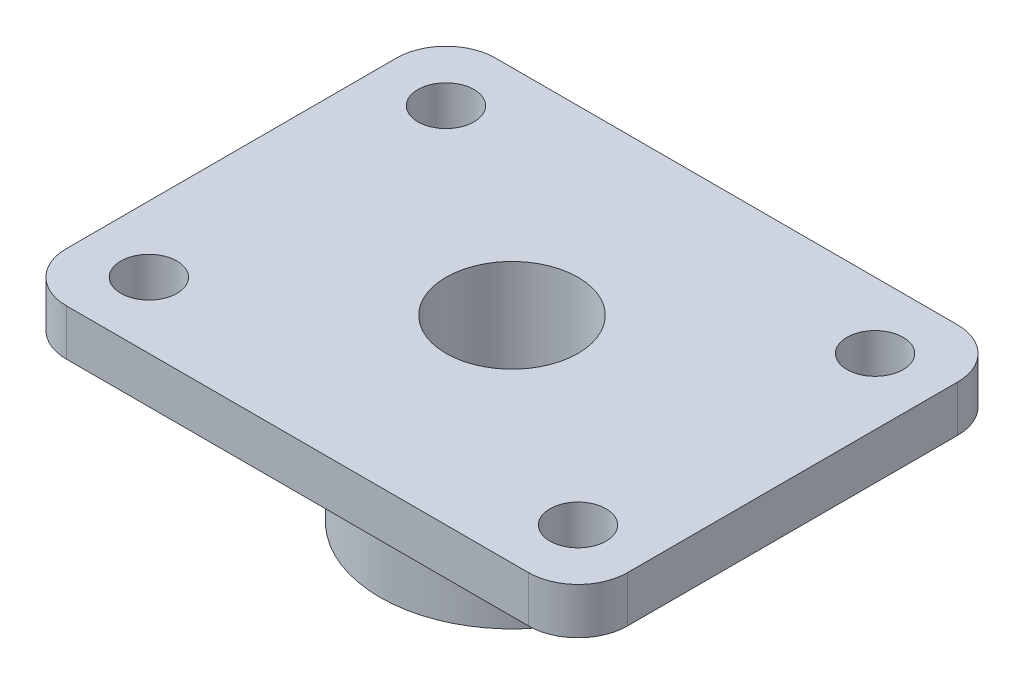
SolidWorks part; units mm, degrees
material "Acciaio al carbonio semplice"
ref_plane "Piano frontale" through (0, 0, 0) normal (0, 0, 1) x (1, 0, 0)
ref_plane "Piano superiore" through (0, 0, 0) normal (0, 1, 0) x (1, 0, 0)
ref_plane "Piano destro" through (0, 0, 0) normal (1, 0, 0) x (0, 0, -1)
sketch "Schizzo1" plane through (0, 0, 0) normal (0, 1, 0) x (1, 0, 0)
  line L0 (0, 0) -> (85, 0) construction
  line L1 (-70, 65) -> (70, 65)
  line L2 (-85, 50) -> (-85, -50)
  line L3 (-70, -65) -> (70, -65)
  line L4 (85, 50) -> (85, -50)
  line L5 (-85, 65) -> (85, -65) construction
  line L6 (-85, -65) -> (85, 65) construction
  line L7 (0, 0) -> (0, -65) construction
  circle A0 centre (0, 0) radius 20
  circle A1 centre (65, -45) radius 8.5
  arc A2 (70, -65) -> (85, -50) centre (70, -50) ccw
  circle A3 centre (65, 45) radius 8.5
  circle A4 centre (-65, -45) radius 8.5
  circle A5 centre (-65, 45) radius 8.5
  arc A6 (-85, -50) -> (-70, -65) centre (-70, -50) ccw
  arc A7 (70, 65) -> (85, 50) centre (70, 50) cw
  arc A8 (-70, 65) -> (-85, 50) centre (-70, 50) ccw
  point P0 (0, 0)
  dimension "D3" = 40
  dimension "D4" = 17
  dimension "D7" = 15
  dimension "D8" = 15
  dimension "D1" = 170
  dimension "D2" = 130
  dimension "D5" = 20
  dimension "D6" = 20
extrude "Estrusione-Estrusione1" add sketch "Schizzo1" along normal blind 14
sketch "Schizzo2" plane through (0, 0, 0) normal (0, -1, 0) x (1, 0, 0)
  circle A0 centre (0, 0) radius 40
  circle A1 centre (0, 0) radius 20
  dimension "D1" = 80
  dimension "D2" = 40
extrude "Estrusione-Estrusione2" add sketch "Schizzo2" along normal blind 40
